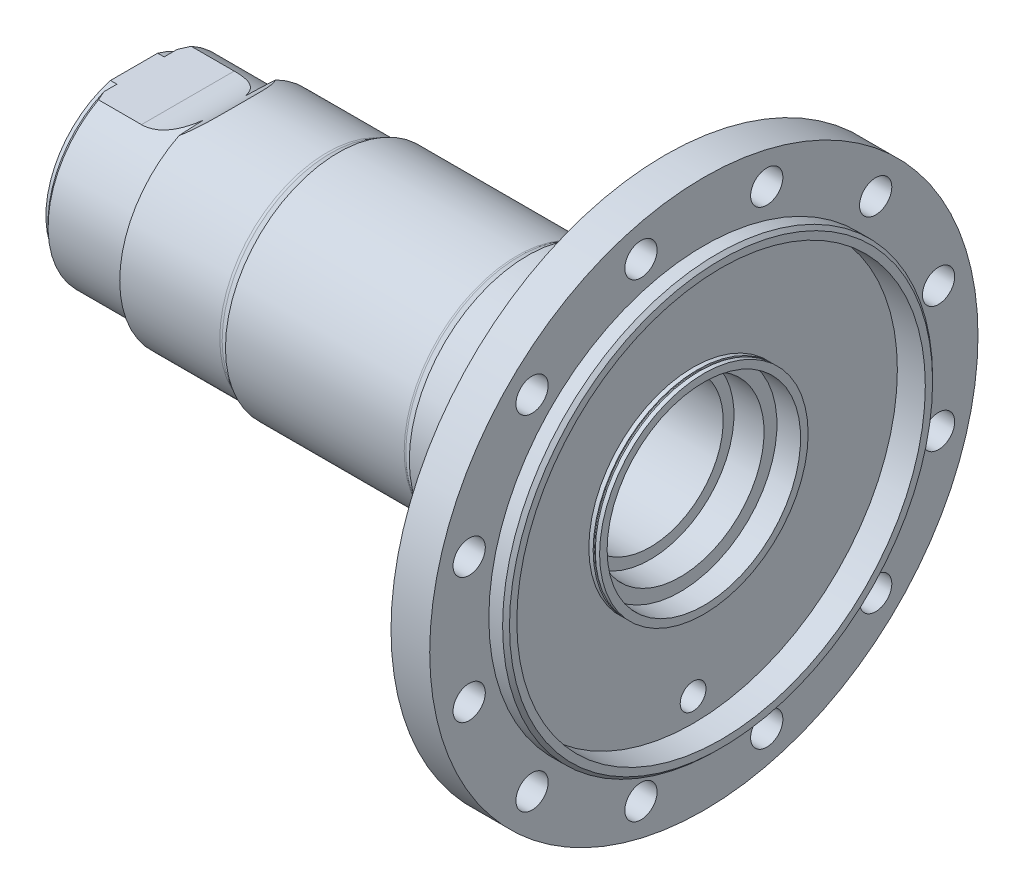
SolidWorks part; units mm, degrees
ref_plane "Спереди" through (0, 0, 0) normal (0, 0, 1) x (1, 0, 0)
ref_plane "Сверху" through (0, 0, 0) normal (0, 1, 0) x (1, 0, 0)
ref_plane "Справа" through (0, 0, 0) normal (1, 0, 0) x (0, 0, -1)
sketch "Эскиз1" plane through (0, 0, 0) normal (0, 0, 1) x (1, 0, 0)
  line L0 (0, 0) -> (273, 0)
  line L1 (0, 0) -> (0, 41)
  line L2 (0, 41) -> (3, 41)
  line L3 (3, 41) -> (3, 43)
  line L4 (3, 43) -> (5, 45)
  line L5 (5, 45) -> (42, 45)
  line L6 (42, 45) -> (43.3397, 50)
  line L7 (43.3397, 50) -> (89.866, 50)
  line L8 (91.366, 50.4019) -> (95, 52.5)
  line L9 (95, 52.5) -> (178.134, 52.5)
  line L10 (179.134, 52.7679) -> (183, 55)
  line L11 (183, 55) -> (213, 55)
  line L12 (215, 57) -> (215, 60.7679)
  line L13 (215, 60.7679) -> (218, 62.5)
  line L14 (218, 62.5) -> (237, 62.5)
  line L15 (239, 64.5) -> (239, 65.5)
  line L16 (239, 65.5) -> (240.4142, 66.9142)
  line L17 (241, 68.3284) -> (241, 78)
  line L18 (241, 78) -> (244.4142, 81.4142)
  line L19 (245, 82.8284) -> (245, 92)
  line L20 (245, 92) -> (246.4142, 93.4142)
  line L21 (247, 94.8284) -> (247, 127.5)
  line L22 (247, 127.5) -> (265, 127.5)
  line L23 (265, 127.5) -> (265, 100)
  line L24 (265, 100) -> (271.4, 100)
  line L25 (271.4, 100) -> (273, 98.4)
  line L26 (273, 98.4) -> (273, 0)
  arc A0 (89.866, 50) -> (91.366, 50.4019) centre (89.866, 53) ccw
  arc A1 (178.134, 52.5) -> (179.134, 52.7679) centre (178.134, 54.5) ccw
  arc A2 (213, 55) -> (215, 57) centre (213, 57) ccw
  arc A3 (237, 62.5) -> (239, 64.5) centre (237, 64.5) ccw
  arc A4 (240.4142, 66.9142) -> (241, 68.3284) centre (239, 68.3284) ccw
  arc A5 (244.4142, 81.4142) -> (245, 82.8284) centre (243, 82.8284) ccw
  arc A6 (246.4142, 93.4142) -> (247, 94.8284) centre (245, 94.8284) ccw
revolve "Повернуть1" add sketch "Эскиз1" angle 360 about L0
sketch "Эскиз2" plane through (0, 0, 0) normal (0, 0, 1) x (1, 0, 0)
  line L0 (0, 0) -> (273, 0)
  line L1 (0, 0) -> (0, 32.7321)
  line L2 (0, 32.7321) -> (3, 31)
  line L3 (3, 31) -> (203.5, 31)
  line L4 (203.5, 31) -> (203.5, 34)
  line L5 (203.5, 34) -> (240, 34)
  line L6 (240, 34) -> (240, 39)
  line L7 (240, 39) -> (254, 39)
  line L8 (254, 39) -> (254, 45)
  line L9 (254, 45) -> (265, 45)
  line L10 (265, 45) -> (265, 95)
  line L11 (265, 95) -> (273, 95)
  line L12 (273, 95) -> (273, 0)
revolve "Вырез-Повернуть1" cut sketch "Эскиз2" angle 360 about L0
sketch "Эскиз3" plane through (0, 0, 0) normal (0, 0, 1) x (1, 0, 0)
  line L0 (0, 0) -> (273, 0) construction
  line L1 (260, 48.5) -> (262, 48.5)
  line L2 (262, 48.5) -> (262, 95)
  line L3 (262, 95) -> (260, 95)
  line L4 (260, 95) -> (260, 48.5)
revolve "Rear_recess_left" cut sketch "Эскиз3" angle 360 about L0
sketch "Эскиз4" plane through (0, 0, 0) normal (0, 0, 1) x (1, 0, 0)
  line L0 (0, 0) -> (273, 0) construction
  line L1 (263, 48) -> (263, 95)
  line L2 (263, 95) -> (262, 95)
  line L3 (262, 95) -> (262, 48)
  arc A0 (262, 48) -> (262.5, 47.5) centre (262.5, 48) ccw
  arc A1 (262.5, 47.5) -> (263, 48) centre (262.5, 48) ccw
revolve "Collar_groove_nominal" cut sketch "Эскиз4" angle 360 about L0
sketch "Эскиз5" plane through (0, 0, 0) normal (0, 0, 1) x (1, 0, 0)
  line L0 (0, 0) -> (273, 0) construction
  line L1 (263, 48.5) -> (265, 48.5)
  line L2 (265, 48.5) -> (265, 95)
  line L3 (265, 95) -> (263, 95)
  line L4 (263, 95) -> (263, 48.5)
revolve "Rear_recess_lip" cut sketch "Эскиз5" angle 360 about L0
sketch "Эскиз6" plane through (0, 0, 0) normal (1, 0, 0) x (0, 0, -1)
  circle A0 centre (109.1496, 29.2466) radius 7.5
extrude "Вырез-Вытянуть1" cut sketch "Эскиз6" along normal through all
sketch "Эскиз7" plane through (0, 0, 0) normal (1, 0, 0) x (0, 0, -1)
  circle A0 centre (79.9031, 79.9031) radius 7.5
extrude "Вырез-Вытянуть2" cut sketch "Эскиз7" along normal through all
sketch "Эскиз8" plane through (0, 0, 0) normal (1, 0, 0) x (0, 0, -1)
  circle A0 centre (29.2466, 109.1496) radius 7.5
extrude "Вырез-Вытянуть3" cut sketch "Эскиз8" along normal through all
sketch "Эскиз9" plane through (0, 0, 0) normal (1, 0, 0) x (0, 0, -1)
  circle A0 centre (-29.2466, 109.1496) radius 7.5
extrude "Вырез-Вытянуть4" cut sketch "Эскиз9" along normal through all
sketch "Эскиз10" plane through (0, 0, 0) normal (1, 0, 0) x (0, 0, -1)
  circle A0 centre (-79.9031, 79.9031) radius 7.5
extrude "Вырез-Вытянуть5" cut sketch "Эскиз10" along normal through all
sketch "Эскиз11" plane through (0, 0, 0) normal (1, 0, 0) x (0, 0, -1)
  circle A0 centre (-109.1496, 29.2466) radius 7.5
extrude "Вырез-Вытянуть6" cut sketch "Эскиз11" along normal through all
sketch "Эскиз12" plane through (0, 0, 0) normal (1, 0, 0) x (0, 0, -1)
  circle A0 centre (-109.1496, -29.2466) radius 7.5
extrude "Вырез-Вытянуть7" cut sketch "Эскиз12" along normal through all
sketch "Эскиз13" plane through (0, 0, 0) normal (1, 0, 0) x (0, 0, -1)
  circle A0 centre (-79.9031, -79.9031) radius 7.5
extrude "Вырез-Вытянуть8" cut sketch "Эскиз13" along normal through all
sketch "Эскиз14" plane through (0, 0, 0) normal (1, 0, 0) x (0, 0, -1)
  circle A0 centre (-29.2466, -109.1496) radius 7.5
extrude "Вырез-Вытянуть9" cut sketch "Эскиз14" along normal through all
sketch "Эскиз15" plane through (0, 0, 0) normal (1, 0, 0) x (0, 0, -1)
  circle A0 centre (29.2466, -109.1496) radius 7.5
extrude "Вырез-Вытянуть10" cut sketch "Эскиз15" along normal through all
sketch "Эскиз16" plane through (0, 0, 0) normal (1, 0, 0) x (0, 0, -1)
  circle A0 centre (79.9031, -79.9031) radius 7.5
extrude "Вырез-Вытянуть11" cut sketch "Эскиз16" along normal through all
sketch "Эскиз17" plane through (0, 0, 0) normal (1, 0, 0) x (0, 0, -1)
  circle A0 centre (109.1496, -29.2466) radius 7.5
extrude "Вырез-Вытянуть12" cut sketch "Эскиз17" along normal through all
sketch "Эскиз18" plane through (0, 0, 0) normal (1, 0, 0) x (0, 0, -1)
  circle A0 centre (0, -84) radius 6
extrude "Вырез-Вытянуть13" cut sketch "Эскиз18" along normal through all
sketch "Эскиз19" plane through (0, 0, 0) normal (0, 0, 1) x (1, 0, 0)
  line L0 (-1, 39.5) -> (25, 39.5)
  line L1 (60, 74.5) -> (60, 150)
  line L2 (60, 150) -> (-1, 150)
  line L3 (-1, 150) -> (-1, 39.5)
  arc A0 (25, 39.5) -> (60, 74.5) centre (25, 74.5) ccw
extrude "Left_flat_84_5_R35" cut sketch "Эскиз19" against normal through all and the other way through all
sketch "Эскиз20" plane through (0, 0, 0) normal (0, 0, 1) x (1, 0, 0)
  line L0 (-1, -25) -> (3, -25)
  line L1 (3, -25) -> (3, -100)
  line L2 (3, -100) -> (-1, -100)
  line L3 (-1, -100) -> (-1, -25)
extrude "Left_end_bottom_20" cut sketch "Эскиз20" against normal through all and the other way through all
